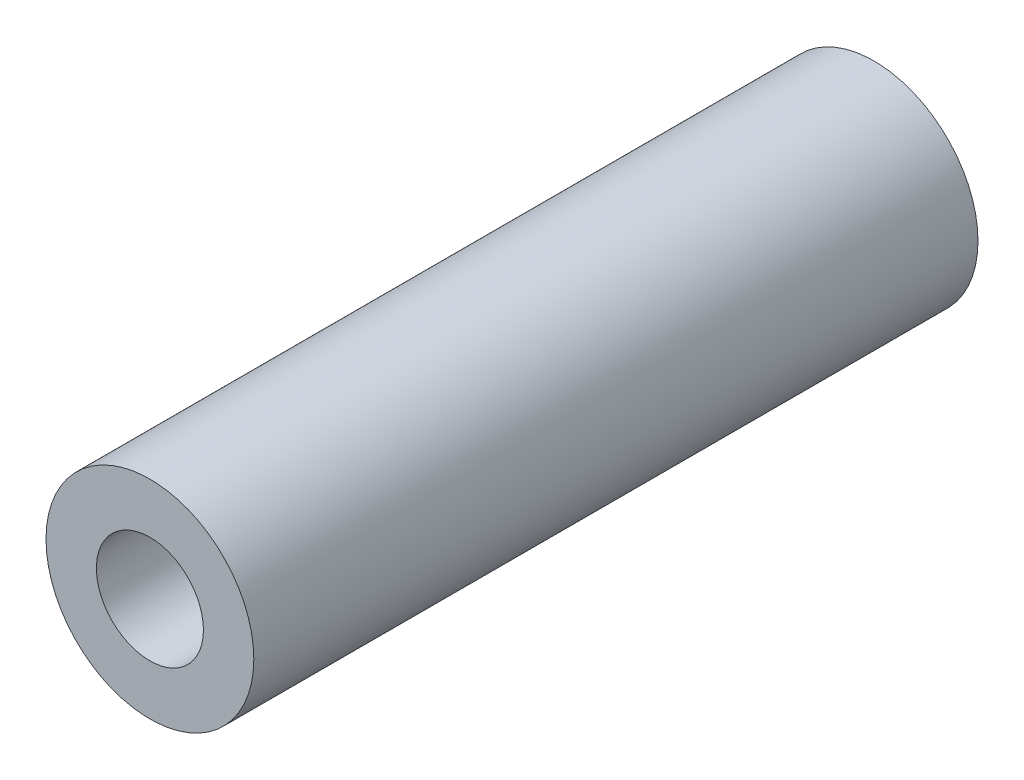
SolidWorks part; units mm, degrees
ref_plane "Front Plane" through (0, 0, 0) normal (0, 0, 1) x (1, 0, 0)
ref_plane "Top Plane" through (0, 0, 0) normal (0, 1, 0) x (1, 0, 0)
ref_plane "Right Plane" through (0, 0, 0) normal (1, 0, 0) x (0, 0, -1)
sketch "Sketch1" plane through (0, 0, 0) normal (0, 0, 1) x (1, 0, 0)
  circle A0 centre (0, 0) radius 3.3
  circle A1 centre (0, 0) radius 1.7
  dimension "D1" = 6.6
  dimension "D2" = 3.4
extrude "Boss-Extrude1" add sketch "Sketch1" along normal blind 23
